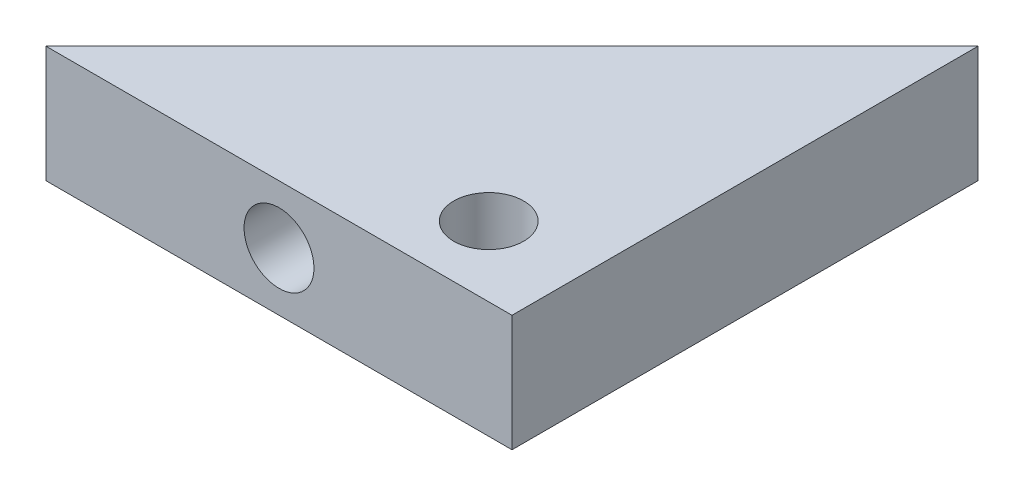
SolidWorks part; units mm, degrees
ref_plane "Front Plane" through (0, 0, 0) normal (0, 0, 1) x (1, 0, 0)
ref_plane "Top Plane" through (0, 0, 0) normal (0, 1, 0) x (1, 0, 0)
ref_plane "Right Plane" through (0, 0, 0) normal (1, 0, 0) x (0, 0, -1)
sketch "Sketch1" plane through (0, 0, 0) normal (0, 1, 0) x (1, 0, 0)
  line L0 (0, 0) -> (-20, 0)
  line L1 (-20, 0) -> (0, 20)
  line L2 (0, 0) -> (0, 20)
  dimension "D1" = 45
  dimension "D2" = 20
extrude "Boss-Extrude1" add sketch "Sketch1" along normal blind 5
sketch "Sketch2" plane through (0, 0, 0) normal (0, 0, 1) x (1, 0, 0)
  line L0 (-20, 2.5) -> (-14.1253, 2.5) construction
  line L1 (-20, 5) -> (-20, 0) construction
  circle A0 centre (-10, 2.5) radius 1.5
  dimension "D1" = 3
  dimension "D2" = 10
extrude "Cut-Extrude1" cut sketch "Sketch2" against normal blind 7
sketch "Sketch3" plane through (-10, 0, -10) normal (-0.7071, 0, -0.7071) x (-0.7071, 0, 0.7071)
  line L0 (-14.1421, 2.5) -> (14.1421, 2.5) construction
  line L1 (-14.1421, 5) -> (-14.1421, 0) construction
  line L2 (14.1421, 5) -> (14.1421, 0) construction
  circle A0 centre (-3.3579, 2.5) radius 1.5
  dimension "D1" = 3
  dimension "D2" = 17.5
extrude "Cut-Extrude2" cut sketch "Sketch3" against normal blind 7
sketch "Sketch4" plane through (0, 5, 0) normal (0, 1, 0) x (1, 0, 0)
  line L0 (-20, 0) -> (0, 0) construction
  line L1 (0, 0) -> (0, 20) construction
  circle A0 centre (-4, 3) radius 1.5
  dimension "D1" = 3
  dimension "D2" = 3
  dimension "D3" = 4
extrude "Cut-Extrude3" cut sketch "Sketch4" against normal blind 7
